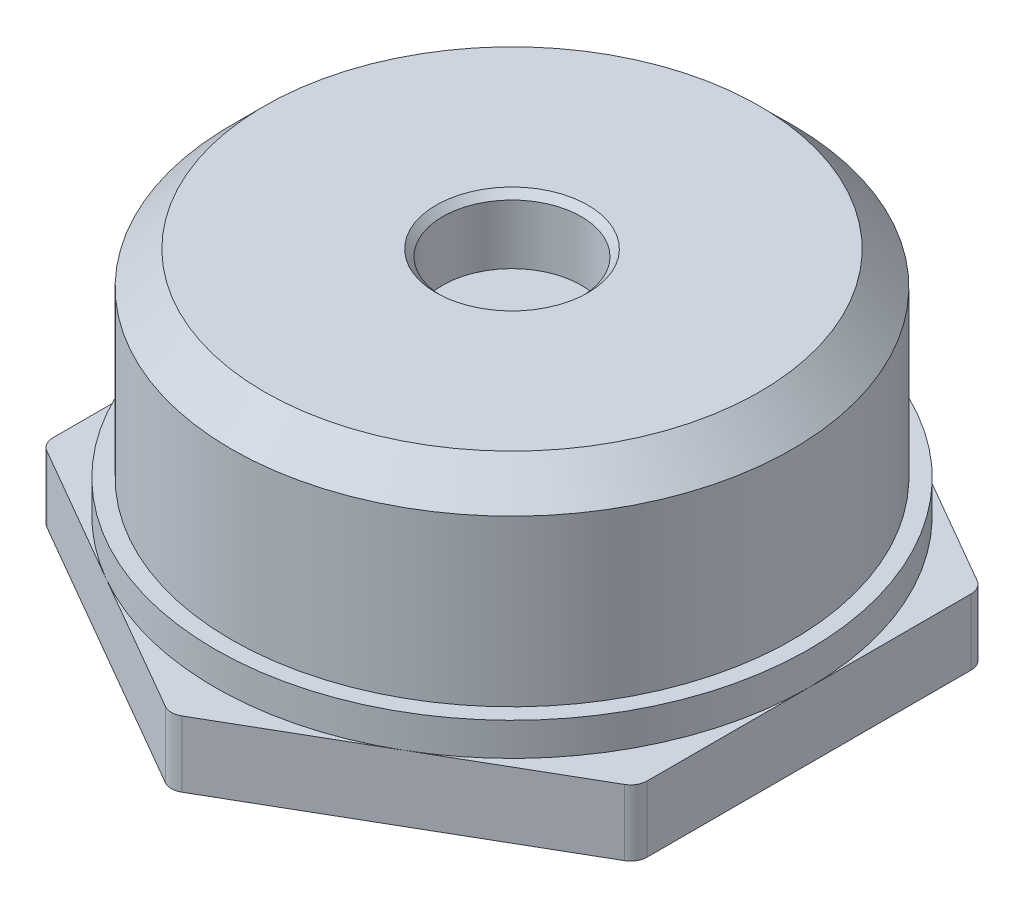
SolidWorks part; units mm, degrees
material "ABS"
ref_plane "Front Plane" through (0, 0, 0) normal (0, 0, 1) x (1, 0, 0)
ref_plane "Top Plane" through (0, 0, 0) normal (0, 1, 0) x (1, 0, 0)
ref_plane "Right Plane" through (0, 0, 0) normal (1, 0, 0) x (0, 0, -1)
ref_plane "Plane2" through (0, 31, 0) normal (0, 1, 0) x (1, 0, 0)
sketch "Sketch1" plane through (0, 31, 0) normal (0, 1, 0) x (1, 0, 0)
  line L1 (0, 10.3923) -> (-9, 5.1962)
  line L2 (-9, 5.1962) -> (-9, -5.1962)
  line L3 (-9, -5.1962) -> (0, -10.3923)
  line L4 (0, -10.3923) -> (9, -5.1962)
  line L5 (9, -5.1962) -> (9, 5.1962)
  line L6 (9, 5.1962) -> (0, 10.3923)
  circle A0 centre (0, 0) radius 9 construction
  dimension "D1" = 18
extrude "Boss-Extrude1" add sketch "Sketch1" along normal blind 2
fillet "Fillet1" radius 0.5 6 edges at (0, 32, -10.3923) (-9, 32, -5.1962) (-9, 32, 5.1962) (0, 32, 10.3923) (9, 32, 5.1962) (9, 32, -5.1962)
sketch "Sketch2" plane through (0, 33, 0) normal (0, 1, 0) x (1, 0, 0)
  circle A1 centre (0, 0) radius 9
  dimension "D2" = 18
extrude "Boss-Extrude2" add sketch "Sketch2" along normal blind 1 contours A1
sketch "Sketch3" plane through (0, 34, 0) normal (0, 1, 0) x (1, 0, 0)
  circle A0 centre (0, 0) radius 8.5
  dimension "D1" = 17
extrude "Boss-Extrude3" add sketch "Sketch3" along normal blind 4
sketch "Sketch4" plane through (0, 38, 0) normal (0, 1, 0) x (1, 0, 0)
  line L1 (0, 2.8868) -> (-2.5, 1.4434)
  line L2 (-2.5, 1.4434) -> (-2.5, -1.4434)
  line L3 (-2.5, -1.4434) -> (0, -2.8868)
  line L4 (0, -2.8868) -> (2.5, -1.4434)
  line L5 (2.5, -1.4434) -> (2.5, 1.4434)
  line L6 (2.5, 1.4434) -> (0, 2.8868)
  circle A0 centre (0, 0) radius 2.5 construction
  dimension "D1" = 5
extrude "Cut-Extrude1" cut sketch "Sketch4" against normal through all
sketch "Sketch5" plane through (0, 38, 0) normal (0, 1, 0) x (1, 0, 0)
  circle A0 centre (0, 0) radius 8.5
  circle A1 centre (0, 0) radius 8.5 construction
extrude "Boss-Extrude4" add sketch "Sketch5" along normal blind 1 and the other way blind 1
sketch "Sketch6" plane through (0, 39, 0) normal (0, 1, 0) x (1, 0, 0)
  circle A1 centre (0, 0) radius 8.5
  circle A2 centre (0, 0) radius 8.5 construction
extrude "Boss-Extrude5" add sketch "Sketch6" along normal blind 1
chamfer "Chamfer2" distance 1 angle 45 1 edges at (0, 40, 8.5)
sketch "Sketch7" plane through (0, 40, 0) normal (0, 1, 0) x (1, 0, 0)
  circle A0 centre (0, 0) radius 2.1
  dimension "D1" = 4.2
extrude "Cut-Extrude2" cut sketch "Sketch7" against normal blind 2
chamfer "Chamfer3" distance 0.2 angle 45 1 edges at (0, 40, 2.1)
